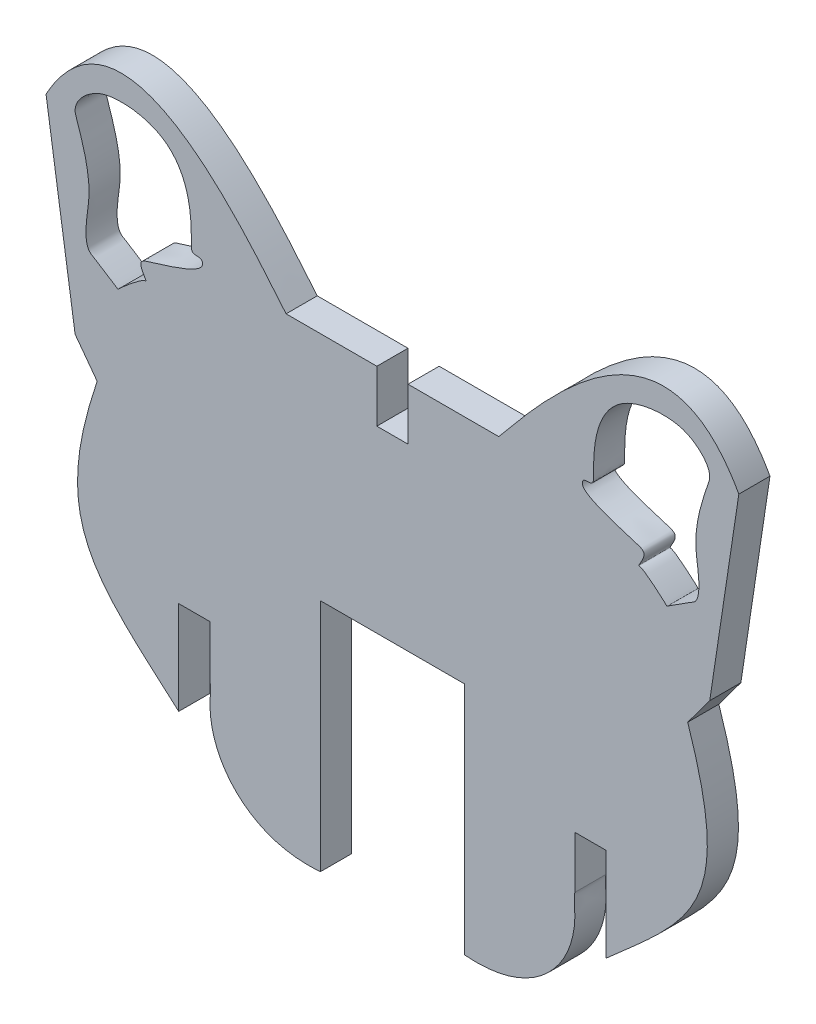
SolidWorks part; units mm, degrees
ref_plane "Front Plane" through (0, 0, 0) normal (0, 0, 1) x (1, 0, 0)
ref_plane "Top Plane" through (0, 0, 0) normal (0, 1, 0) x (1, 0, 0)
ref_plane "Right Plane" through (0, 0, 0) normal (1, 0, 0) x (0, 0, -1)
sketch "Sketch1" plane through (0, 0, 0) normal (0, 0, 1) x (1, 0, 0)
  line L0 (-28.9504, 189.3172) -> (255.8294, 189.3172) construction
  line L1 (-6.9235, 0) -> (6.9235, 0)
  line L2 (-6.9235, 0) -> (-6.9235, -22.594)
  line L3 (0, -22.2758) -> (0, 22.2758) construction
  line L4 (1.5, 17.2758) -> (-1.5, 17.2758)
  line L5 (-1.5, 17.2758) -> (-1.5, 22.2758)
  line L6 (-1.5, 22.2758) -> (-10.2408, 22.2758)
  line L7 (-33.3624, 29.0386) -> (-30.5612, 10.4102)
  line L8 (-30.5612, 10.4102) -> (-28.4383, 7.5526)
  line L9 (-20.583, -16.059) -> (-20.583, -12.059)
  line L10 (6.9235, 0) -> (6.9235, -22.594)
  line L11 (20.583, -16.059) -> (20.583, -12.059)
  line L12 (30.5612, 10.4102) -> (28.4383, 7.5526)
  line L13 (33.3624, 29.0386) -> (30.5612, 10.4102)
  line L14 (1.5, 22.2758) -> (10.2408, 22.2758)
  line L15 (1.5, 17.2758) -> (1.5, 22.2758)
  line L16 (-17.583, -12.059) -> (-20.583, -12.059) construction
  line L17 (-17.583, -12.059) -> (-17.583, -17.059) construction
  line L18 (0, 0) -> (-17.583, -12.059) construction
  line L19 (17.583, -12.059) -> (20.583, -12.059)
  line L20 (-17.583, -12.059) -> (-20.583, -12.059)
  line L21 (-17.583, -12.059) -> (-17.583, -7.064)
  line L22 (-17.583, -7.064) -> (-20.583, -7.064)
  line L23 (-20.583, -12.059) -> (-20.583, -7.064)
  line L24 (20.583, -12.059) -> (20.583, -7.064)
  line L25 (17.583, -7.064) -> (20.583, -7.064)
  line L26 (17.583, -12.059) -> (17.583, -7.064)
  spline S0 degree 3 poles (-10.2408, 22.2758) (-15.1353, 28.2082) (-26.2071, 42.0099) (-33.3624, 29.0386) knots 0 0 0 0 1 1 1 1
  spline S1 degree 3 poles (-28.4383, 7.5526) (-32.9976, -6.0186) (-28.8809, -8.7367) (-20.583, -16.059) knots 0 0 0 0 1 1 1 1
  spline S2 degree 3 poles (-20.583, -12.059) (-20.5558, -12.0474) (-17.179, -10.786) (-18.3912, -17.9068) (-13.6515, -23.2181) (-6.9235, -22.594) knots 0 0 0 0 0.188319 0.288319 1 1 1 1
  spline S3 degree 3 poles (20.583, -12.059) (20.5558, -12.0474) (17.179, -10.786) (18.3912, -17.9068) (13.6515, -23.2181) (6.9235, -22.594) knots 0 0 0 0 0.188319 0.288319 1 1 1 1
  spline S4 degree 3 poles (28.4383, 7.5526) (32.9976, -6.0186) (28.8809, -8.7367) (20.583, -16.059) knots 0 0 0 0 1 1 1 1
  spline S5 degree 3 poles (10.2408, 22.2758) (15.1353, 28.2082) (26.2071, 42.0099) (33.3624, 29.0386) knots 0 0 0 0 1 1 1 1
  spline S6 degree 3 poles (-29.7981, 26.7214) (-30.8887, 29.7283) (-29.1208, 31.4662) (-26.0647, 32.2617) (-22.484, 31.7833) (-19.115, 27.7824) (-19.4627, 23.3622) (-19.1861, 22.6488) (-18.3562, 22.9943) (-18.1293, 21.6708) (-21.3301, 20.6374) (-24.7039, 19.6398) (-23.5858, 18.2097) (-24.1098, 18.3194) (-26.5365, 16.1979) (-26.3805, 16.2156) (-28.3231, 17.4662) (-29.7172, 18.2368) (-29.4573, 20.6482) (-28.9843, 23.9704) (-29.7981, 26.7214) (-30.8887, 29.7283) (-29.1208, 31.4662) knots -0.127442 -0.109104 -0.012123 0 0.048901 0.062539 0.128175 0.147398 0.235552 0.259496 0.362889 0.398352 0.578667 0.606537 0.649187 0.665467 0.753062 0.769272 0.811359 0.822835 0.872558 0.890896 0.987877 1 1.048901 1.062539 1.128175 only from (-30.5612, 29.0386) to (-30.5612, 29.0386)
  spline S7 degree 3 poles (29.7981, 26.7214) (30.8887, 29.7283) (29.1208, 31.4662) (26.0647, 32.2617) (22.484, 31.7833) (19.115, 27.7824) (19.4627, 23.3622) (19.1861, 22.6488) (18.3562, 22.9943) (18.1293, 21.6708) (21.3301, 20.6374) (24.7039, 19.6398) (23.5858, 18.2097) (24.1098, 18.3194) (26.5365, 16.1979) (26.3805, 16.2156) (28.3231, 17.4662) (29.7172, 18.2368) (29.4573, 20.6482) (28.9843, 23.9704) (29.7981, 26.7214) (30.8887, 29.7283) (29.1208, 31.4662) knots -0.127442 -0.109104 -0.012123 0 0.048901 0.062539 0.128175 0.147398 0.235552 0.259496 0.362889 0.398352 0.578667 0.606537 0.649187 0.665467 0.753062 0.769272 0.811359 0.822835 0.872558 0.890896 0.987877 1 1.048901 1.062539 1.128175 only from (30.5612, 29.0386) to (30.5612, 29.0386)
  point P6 (0, 0)
  point P10 (0, 0)
  point P20 (6.9235, -22.594)
  point P33 (0, 17.2758)
  dimension "D4" = 3
  dimension "D5" = 4
  dimension "D9" = 5
  dimension "D1" = 13.847
  dimension "D2" = 22.594
  dimension "D3" = 3
  dimension "D6" = 5
  dimension "D7" = 17.583
  dimension "D8" = 12.059
  dimension "D10" = 4.995
extrude "Boss-Extrude1" add sketch "Sketch1" along normal blind 3 contours S5 L14 L15 L4 L5 L6 S0 L7 L8 S1 L9 L23 L22 L21 S2 L2 L1 L10 S3 L26 L25 L24 L11 S4 L12 L13 S7 S6
